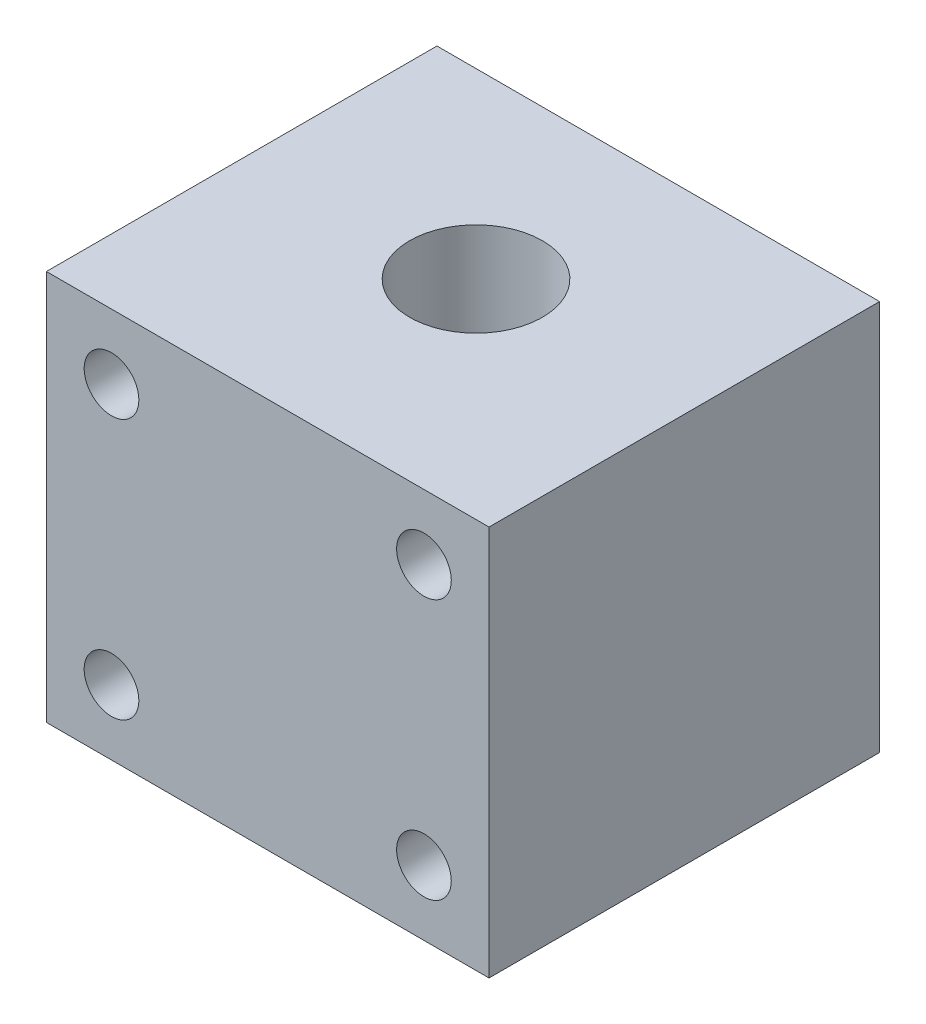
SolidWorks part; units mm, degrees
material "201 退火不锈钢 (SS)"
ref_plane "前视基准面" through (0, 0, 0) normal (0, 0, 1) x (1, 0, 0)
ref_plane "上视基准面" through (0, 0, 0) normal (0, 1, 0) x (1, 0, 0)
ref_plane "右视基准面" through (0, 0, 0) normal (1, 0, 0) x (0, 0, -1)
sketch "草图1" plane through (0, 0, 0) normal (0, 1, 0) x (1, 0, 0)
  line L1 (-17, 15) -> (17, 15)
  line L2 (-17, 15) -> (-17, -15)
  line L3 (-17, -15) -> (17, -15)
  line L4 (17, 15) -> (17, -15)
  line L5 (-17, 15) -> (17, -15) construction
  line L6 (-17, -15) -> (17, 15) construction
  point P0 (0, 0)
  dimension "D1" = 34
  dimension "D2" = 30
extrude "凸台-拉伸1" add sketch "草图1" along normal blind 30
ref_plane "基准面1" through (0, 0, 0) normal (0, -1, 0) x (-1, 0, 0)
sketch "草图2" plane through (0, 0, 0) normal (0, -1, 0) x (-1, 0, 0)
  line L0 (0, 15) -> (0, -15) construction
  line L1 (-17, 15) -> (17, 15) construction
  line L2 (17, -15) -> (-17, -15) construction
  circle A0 centre (0, 1) radius 5.1
  point P9 (0, -2.321)
  dimension "D1" = 10.2
  dimension "D2" = 14
extrude "切除-拉伸1" cut sketch "草图2" against normal through all
sketch "草图3" plane through (0, 0, 0) normal (0, -1, 0) x (-1, 0, 0)
  circle A0 centre (0, 1) radius 8 construction
  circle A1 centre (8, 1) radius 1.55
  circle A2 centre (0, -7) radius 1.55
  circle A3 centre (-8, 1) radius 1.55
  circle A4 centre (0, 9) radius 1.55
  circle A5 centre (0, 1) radius 5.1 construction
  point P5 (0, 0)
  point P6 (-2.1214, 6.2759)
  point P14 (0, 1)
  point P17 (0, 0)
  dimension "D1" = 16
  dimension "D2" = 3.1
  dimension "D3" = 4
extrude "切除-拉伸2" cut sketch "草图3" against normal blind 15
ref_plane "基准面2" through (0, 0, 15) normal (0, 0, 1) x (1, 0, 0)
sketch "草图4" plane through (0, 0, 15) normal (0, 0, 1) x (1, 0, 0)
  line L0 (-17, 30) -> (17, 0) construction
  line L2 (-12, 5) -> (12, 5) construction
  line L3 (-12, 5) -> (-12, 25) construction
  line L4 (-12, 25) -> (12, 25) construction
  line L5 (12, 5) -> (12, 25) construction
  line L6 (-12, 5) -> (12, 25) construction
  line L7 (-12, 25) -> (12, 5) construction
  circle A0 centre (-12, 5) radius 2.1
  circle A1 centre (12, 5) radius 2.1
  circle A2 centre (12, 25) radius 2.1
  circle A3 centre (-12, 25) radius 2.1
  point P4 (0, 15)
  dimension "D3" = 4.2
  dimension "D4" = 4.2
  dimension "D5" = 4.2
  dimension "D6" = 4.2
  dimension "D1" = 24
  dimension "D2" = 20
extrude "切除-拉伸3" cut sketch "草图4" against normal blind 20
